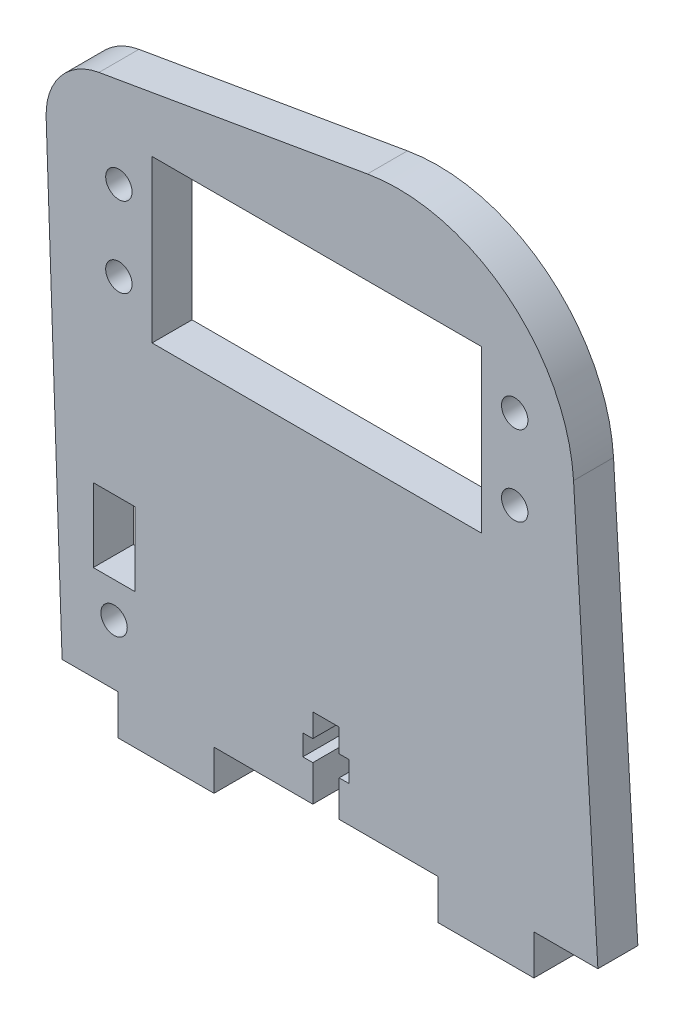
SolidWorks part; units mm, degrees
ref_plane "Спереди" through (0, 0, 0) normal (0, 0, 1) x (1, 0, 0)
ref_plane "Сверху" through (0, 0, 0) normal (0, 1, 0) x (1, 0, 0)
ref_plane "Справа" through (0, 0, 0) normal (1, 0, 0) x (0, 0, -1)
other "Configuration Table"
sketch "Eskiz_kontur" plane through (0, 0, 0) normal (0, 0, 1) x (1, 0, 0)
  line L0 (21.959, 51.3431) -> (25, 0)
  line L1 (-37.3892, 65.8785) -> (-3.8203, 71.6658)
  line L2 (25, 0) -> (17, 0)
  line L3 (17, 0) -> (17, -5)
  line L4 (-42, 0) -> (-43.9951, 57.7208)
  line L5 (17, -5) -> (5, -5)
  line L6 (-35, 0) -> (-42, 0)
  line L7 (5, -5) -> (5, 0)
  line L8 (-35, -5) -> (-35, 0)
  line L9 (5, 0) -> (-7.35, 0)
  line L10 (-23, -5) -> (-35, -5)
  line L11 (-7.35, 0) -> (-7.35, 4.5)
  line L12 (-23, 0) -> (-23, -5)
  line L13 (-7.35, 4.5) -> (-6.1, 4.5)
  line L14 (-10.65, 0) -> (-23, 0)
  line L15 (-6.1, 4.5) -> (-6.1, 7.1)
  line L16 (-10.65, 4.5) -> (-10.65, 0)
  line L17 (-6.1, 7.1) -> (-7.35, 7.1)
  line L18 (-11.9, 4.5) -> (-10.65, 4.5)
  line L19 (-7.35, 7.1) -> (-7.35, 10)
  line L20 (-11.9, 7.1) -> (-11.9, 4.5)
  line L21 (-7.35, 10) -> (-10.65, 10)
  line L22 (-10.65, 7.1) -> (-11.9, 7.1)
  line L23 (-10.65, 10) -> (-10.65, 7.1)
  line L24 (-32.9, 11.9) -> (-32.9, 21.1)
  line L25 (-32.9, 21.1) -> (-38.1, 21.1)
  line L26 (-38.1, 11.9) -> (-32.9, 11.9)
  line L27 (-38.1, 21.1) -> (-38.1, 11.9)
  line L28 (-30.75, 60.1) -> (-30.75, 39.9)
  line L29 (-30.75, 39.9) -> (10.45, 39.9)
  line L30 (10.45, 60.1) -> (-30.75, 60.1)
  line L31 (10.45, 39.9) -> (10.45, 60.1)
  arc A0 (-3.8203, 71.6658) -> (21.959, 51.3431) centre (0, 50) cw
  arc A1 (-43.9951, 57.7208) -> (-37.3892, 65.8785) centre (-36, 58) cw
extrude "Plastina" add sketch "Eskiz_kontur" along normal blind 5
sketch "Eskiz_otverstiya" plane through (0, 0, 0) normal (0, 0, 1) x (1, 0, 0)
  circle A0 centre (-35.5, 7.5) radius 1.65
  circle A1 centre (-34.9, 45) radius 1.65
  circle A2 centre (-34.9, 55) radius 1.65
  circle A3 centre (14.6, 45) radius 1.65
  circle A4 centre (14.6, 55) radius 1.65
  dimension "d1" = 3.3
  dimension "d2" = 3.3
  dimension "d3" = 3.3
  dimension "d4" = 3.3
  dimension "d5" = 3.3
extrude "Otverstiya" cut sketch "Eskiz_otverstiya" against normal through all and the other way through all
equation "\"T3\" = 3"
equation "\"T5\" = 5"
equation "\"D_M3\" = 3.3"
equation "\"D_M2\" = 2.2"
equation "\"D_M3_TAP\" = 2.5"
equation "\"D_M4\" = 4.5"
equation "\"L1\" = 100"
equation "\"L2\" = 100"
equation "\"D1@Plastina\" = \"T5\""
equation "\"d1@Eskiz_otverstiya\" = \"D_M3\""
equation "\"d2@Eskiz_otverstiya\" = \"D_M3\""
equation "\"d3@Eskiz_otverstiya\" = \"D_M3\""
equation "\"d4@Eskiz_otverstiya\" = \"D_M3\""
equation "\"d5@Eskiz_otverstiya\" = \"D_M3\""
